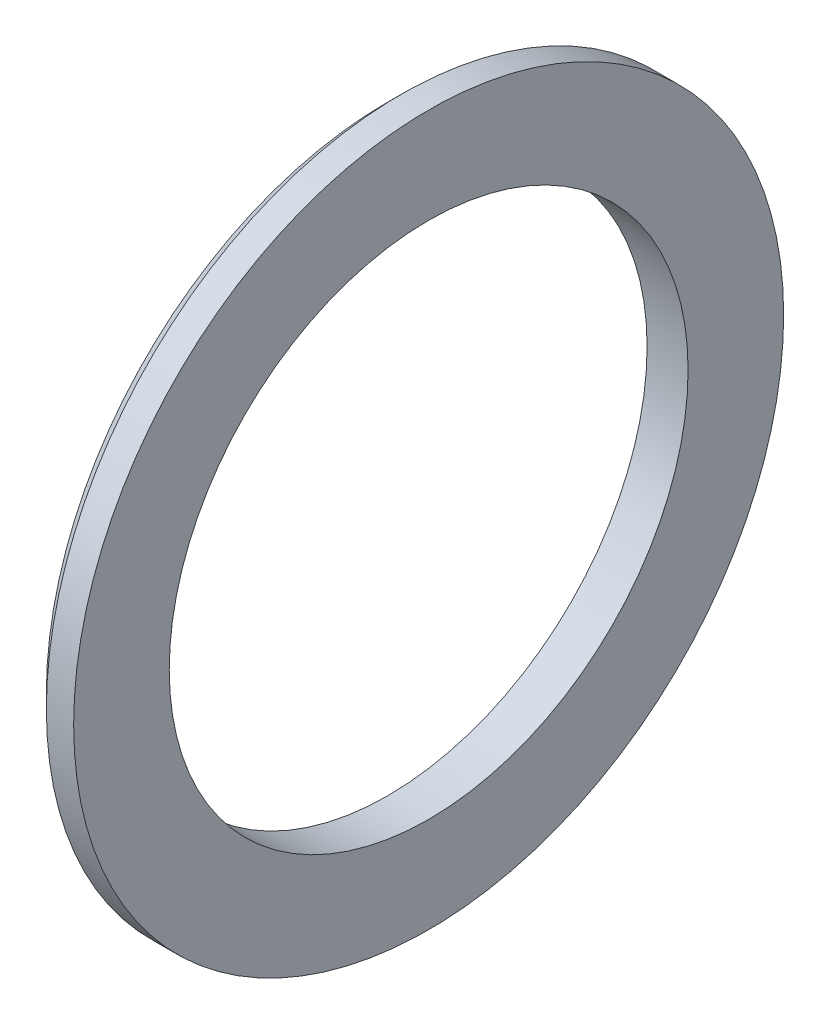
SolidWorks part; units mm, degrees
ref_plane "Спереди" through (0, 0, 0) normal (0, 0, 1) x (1, 0, 0)
ref_plane "Сверху" through (0, 0, 0) normal (0, 1, 0) x (1, 0, 0)
ref_plane "Справа" through (0, 0, 0) normal (1, 0, 0) x (0, 0, -1)
sketch "Эскиз1" plane through (0, 0, 0) normal (0, 0, 1) x (1, 0, 0)
  line L5 (0, 19) -> (0, 25)
  line L6 (0, 25) -> (1, 26)
  line L7 (1, 26) -> (3, 26)
  line L8 (3, 26) -> (3, 19)
  line L9 (3, 19) -> (0, 19)
  line L10 (0, 0) -> (0, 19) construction
  line L11 (0, 0) -> (16163.9124, 0) construction
  point P7 (1.5, 19)
  point P11 (1.5567, 19)
  dimension "D1" = 52
  dimension "D2" = 3
  dimension "D3" = 1
  dimension "D4" = 45
  dimension "D5" = 38
revolve "Повернуть1" add sketch "Эскиз1" angle 360 about L11
